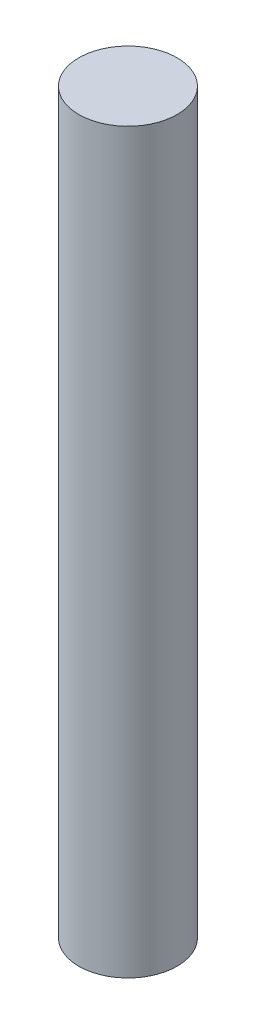
SolidWorks part; units mm, degrees
ref_plane "Front Plane" through (0, 0, 0) normal (0, 0, 1) x (1, 0, 0)
ref_plane "Top Plane" through (0, 0, 0) normal (0, 1, 0) x (1, 0, 0)
ref_plane "Right Plane" through (0, 0, 0) normal (1, 0, 0) x (0, 0, -1)
sketch "Sketch1" plane through (0, 0, 0) normal (0, 1, 0) x (1, 0, 0)
  circle A0 centre (0, 0) radius 10
  dimension "D1" = 20
extrude "Boss-Extrude1" add sketch "Sketch1" along normal blind 150
